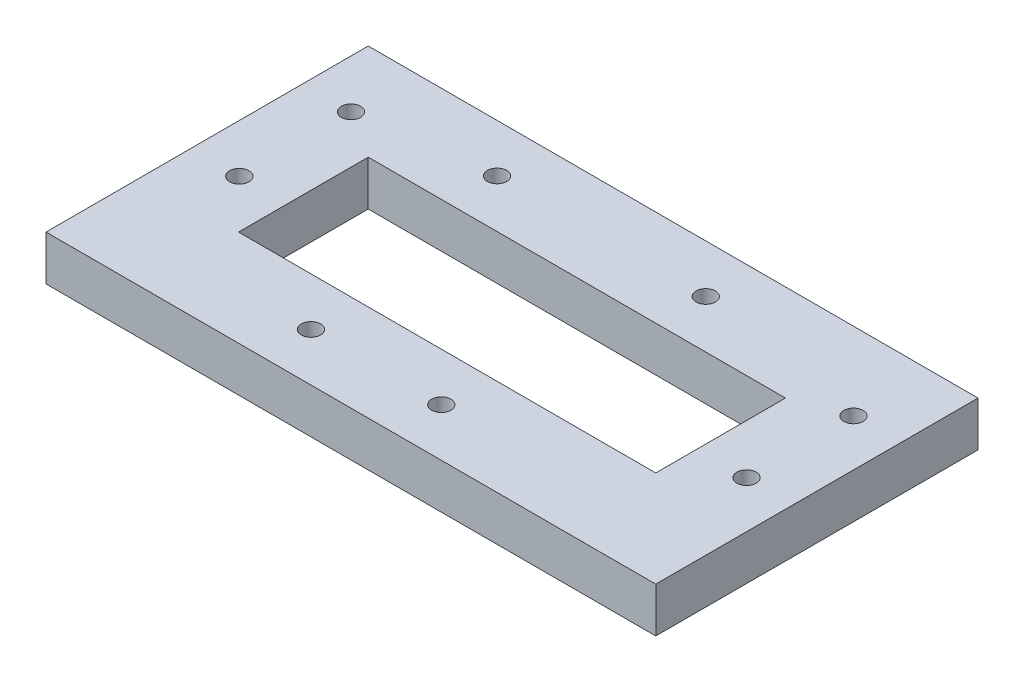
SolidWorks part; units mm, degrees
ref_plane "Front" through (0, 0, 0) normal (0, 0, 1) x (1, 0, 0)
ref_plane "Top" through (0, 0, 0) normal (0, 1, 0) x (1, 0, 0)
ref_plane "Right" through (0, 0, 0) normal (1, 0, 0) x (0, 0, -1)
sketch "Sketch2" plane through (0, 0, 0) normal (0, 1, 0) x (1, 0, 0)
  line L0 (-32.5, 25.1025) -> (-32.5, 10.1025) construction
  line L1 (-47.5, -25.1025) -> (47.5, -25.1025)
  line L2 (-47.5, -25.1025) -> (-47.5, 25.1025)
  line L3 (-47.5, 25.1025) -> (47.5, 25.1025)
  line L4 (47.5, -25.1025) -> (47.5, 25.1025)
  line L5 (-47.5, -25.1025) -> (47.5, 25.1025) construction
  line L6 (-47.5, 25.1025) -> (47.5, -25.1025) construction
  line L7 (-32.5, -10.1025) -> (32.5, -10.1025)
  line L8 (-32.5, -10.1025) -> (-32.5, 10.1025)
  line L9 (-32.5, 10.1025) -> (32.5, 10.1025)
  line L10 (32.5, -10.1025) -> (32.5, 10.1025)
  line L11 (-32.5, -10.1025) -> (32.5, 10.1025) construction
  line L12 (-32.5, 10.1025) -> (32.5, -10.1025) construction
  line L13 (32.5, 10.1025) -> (32.5, 25.1025) construction
  line L14 (-32.5, 17.6025) -> (32.5, 17.6025) construction
  line L15 (32.5, 10.1025) -> (47.5, 10.1025) construction
  line L16 (32.5, -10.1025) -> (47.5, -10.1025) construction
  line L17 (40.2075, 25.1025) -> (40.2075, -25.1025) construction
  line L18 (-47.5, 10.1025) -> (-32.5, 10.1025) construction
  line L19 (-47.5, -10.1025) -> (-32.5, -10.1025) construction
  line L20 (-32.5, -10.1025) -> (-32.5, -25.1025) construction
  line L21 (32.5, -10.1025) -> (32.5, -25.1025) construction
  line L22 (-39.9706, 25.1025) -> (-39.9706, -25.1025) construction
  line L23 (-32.5, -17.6025) -> (32.5, -17.6025) construction
  circle A0 centre (-19.9358, 17.6025) radius 1.5
  circle A1 centre (12.5846, 17.6025) radius 1.5
  circle A2 centre (-39.9706, 14.8779) radius 1.5
  circle A3 centre (-39.9706, -2.5177) radius 1.5
  circle A4 centre (40.2075, 12.9907) radius 1.5
  circle A5 centre (40.2075, -3.6665) radius 1.5
  circle A6 centre (-13.7161, -17.6025) radius 1.5
  circle A7 centre (6.5806, -17.6025) radius 1.5
  point P0 (0, 0)
  point P6 (0, 0)
  point P35 (-39.9706, -2.5177)
  point P38 (40.2075, 12.9907)
  point P41 (40.2075, -3.6665)
  point P44 (0, 0)
  point P45 (-13.7161, -17.6025)
  point P48 (6.5806, -17.6025)
  dimension "D1" = 50.205
extrude "Boss-Extrude2" add sketch "Sketch2" along normal blind 7
